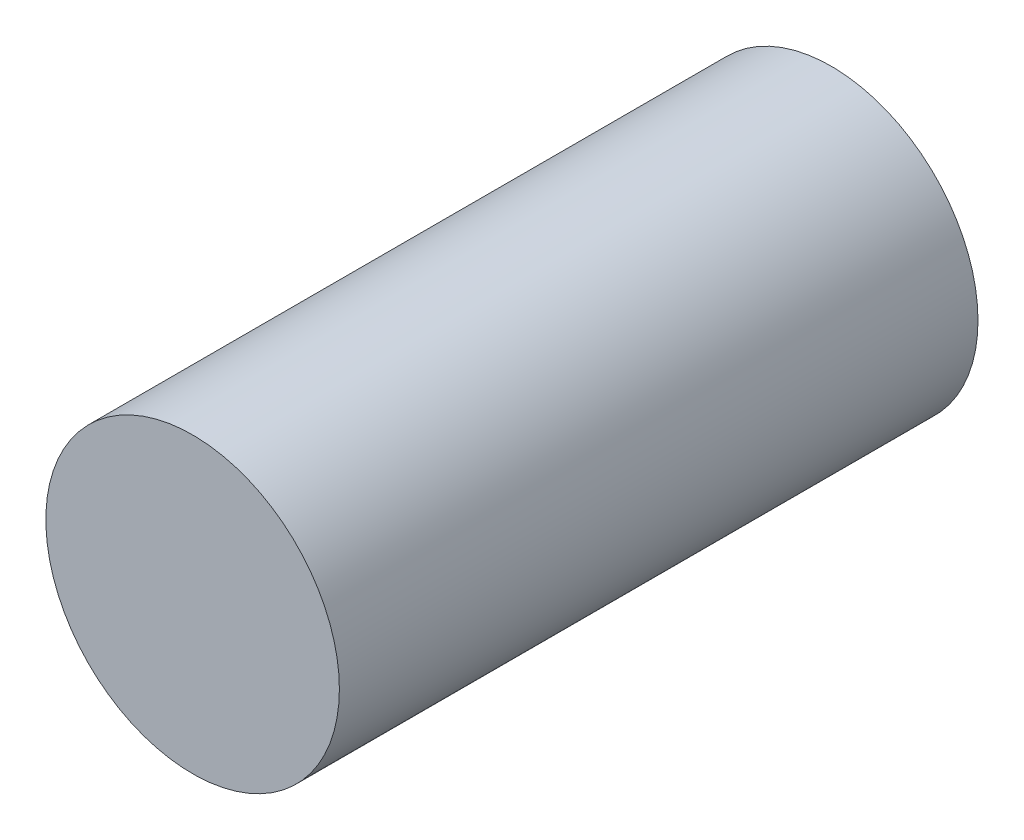
SolidWorks part; units mm, degrees
ref_plane "前基準面" through (0, 0, 0) normal (0, 0, 1) x (1, 0, 0)
ref_plane "上基準面" through (0, 0, 0) normal (0, 1, 0) x (1, 0, 0)
ref_plane "右基準面" through (0, 0, 0) normal (1, 0, 0) x (0, 0, -1)
sketch "草圖1" plane through (0, 0, 0) normal (0, 0, 1) x (1, 0, 0)
  circle A0 centre (0, 0) radius 113.3
  dimension "D1" = 226.6
extrude "填料-伸長1" add sketch "草圖1" along normal blind 493
